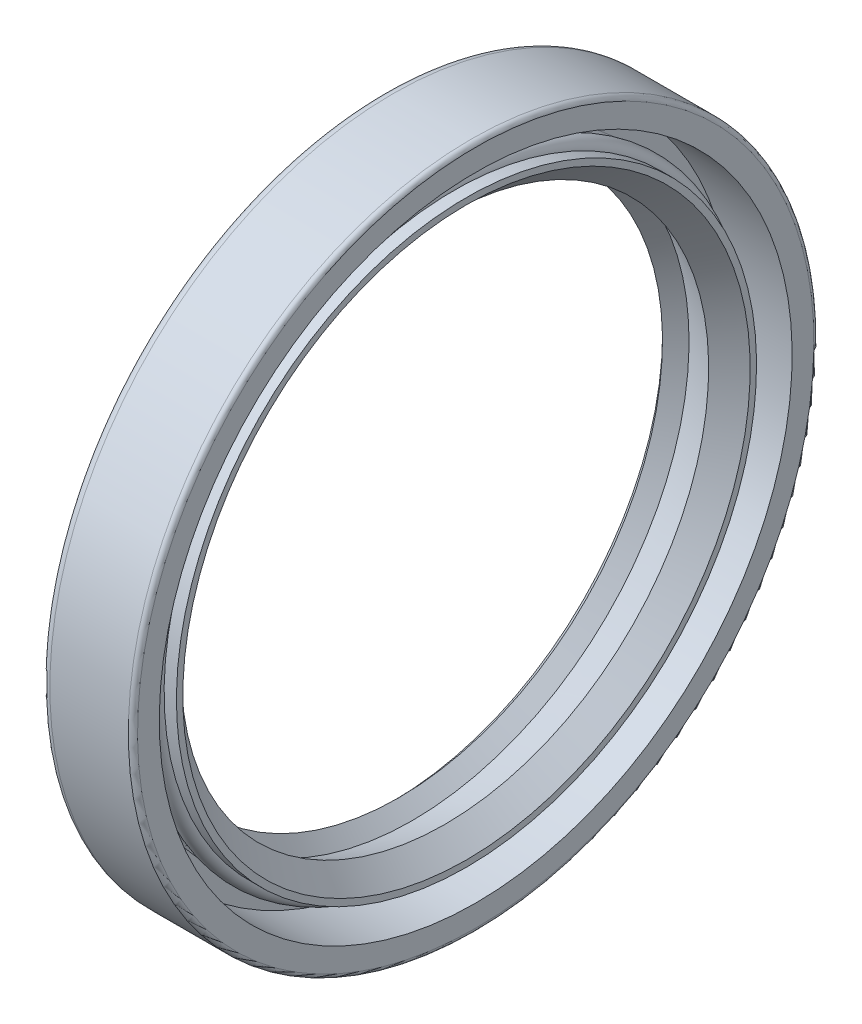
SolidWorks part; units mm, degrees
ref_plane "Front" through (0, 0, 0) normal (0, 0, 1) x (1, 0, 0)
ref_plane "Top" through (0, 0, 0) normal (0, 1, 0) x (1, 0, 0)
ref_plane "Right" through (0, 0, 0) normal (1, 0, 0) x (0, 0, -1)
sketch "Sketch1" plane through (0, 0, 0) normal (0, 0, 1) x (1, 0, 0)
  line L0 (0, 24) -> (0.2188, 24)
  line L1 (0.2188, 24) -> (0.2188, 22)
  line L2 (0.2188, 22) -> (0, 22)
  line L3 (0, 22) -> (0, 21.5)
  line L4 (0, 21.5) -> (1.1667, 21)
  line L5 (1.1667, 21) -> (0.6667, 20.5072)
  line L6 (0.6667, 20.5072) -> (1.1667, 20)
  line L7 (1.1667, 20) -> (2.1813, 21)
  line L8 (2.1813, 21) -> (4.6667, 20)
  line L9 (4.6667, 20) -> (6.3, 21.5167)
  line L10 (6.3, 21.5167) -> (6.3, 22)
  line L11 (6.3, 22) -> (5.3667, 22)
  line L12 (3.9667, 22) -> (2.6833, 22)
  line L13 (2.3333, 22.35) -> (2.3333, 24)
  line L14 (2.3333, 24) -> (7, 24)
  line L15 (7, 24) -> (7, 25.65)
  line L16 (6.65, 26) -> (0.7, 26)
  line L17 (0, 25.3) -> (0, 24)
  line L18 (7, 0) -> (0, 0) construction
  line L19 (1.1667, 20) -> (4.6667, 20) construction
  line L20 (3.675, 26) -> (3.675, 24) construction
  line L21 (3.675, 24) -> (3.675, 22) construction
  line L22 (3.675, 22) -> (3.675, 20) construction
  line L23 (4.6667, 22) -> (4.6667, 20) construction
  line L24 (0, 24.65) -> (2.3333, 24.65) construction
  line L25 (2.3333, 24.65) -> (4.6667, 24.65) construction
  line L26 (4.6667, 24.65) -> (7, 24.65) construction
  line L27 (4.6667, 22) -> (4.6667, 24.65) construction
  line L28 (2.3333, 22.35) -> (2.1813, 21) construction
  line L29 (3.675, 21) -> (2.1813, 21) construction
  line L30 (2.9281, 21) -> (2.9281, 22) construction
  line L31 (2.9281, 21.5) -> (0, 21.5) construction
  line L32 (2.1813, 21) -> (1.1667, 21) construction
  line L33 (1.1667, 20) -> (1.1667, 21) construction
  line L35 (7, 24) -> (7, 22) construction
  line L36 (7, 22) -> (6.3, 22) construction
  line L37 (0, 25.3) -> (0.7, 25.3) construction
  line L39 (1.1667, 24.65) -> (1.1667, 21) construction
  arc A0 (5.3667, 22) -> (3.9667, 22) centre (4.6667, 22) ccw construction
  arc A1 (2.6833, 22) -> (2.3333, 22.35) centre (2.6833, 22.35) cw
  arc A2 (7, 25.65) -> (6.65, 26) centre (6.65, 25.65) ccw
  arc A3 (0.7, 26) -> (0, 25.3) centre (0.7, 25.3) ccw
  arc A4 (3.9667, 22) -> (5.3667, 22) centre (4.6667, 22) ccw
  dimension "D3" = 0.7
  dimension "D4" = 0.35
  dimension "D2" = 0.2188
  dimension "D5" = 67.784
  dimension "D8" = 47.121
revolve "Revolve1" add sketch "Sketch1" angle 360 about L18
sketch "Sketch2" plane through (0, 0, 0) normal (0, 0, 1) x (1, 0, 0)
  line L0 (0, 0) -> (7, 0) construction
  circle A0 centre (4.6667, 22) radius 0.7
revolve "Revolve2" add sketch "Sketch2" angle 360 about L0
equation "\"D2@Sketch1\"=\"SealWidth@Sketch1\"*.03125"
equation "\"D3@Sketch1\"=\"SealWidth@Sketch1\"*.1"
equation "\"D4@Sketch1\"=\"D3@Sketch1\"*.5"
